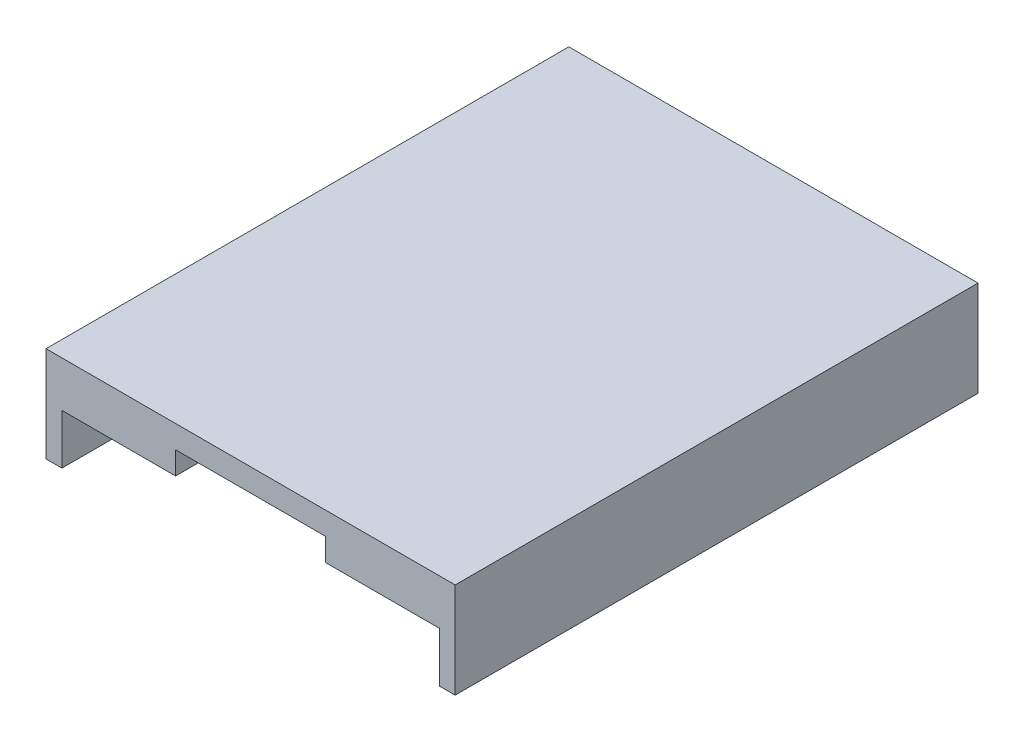
SolidWorks part; units mm, degrees
ref_plane "Front Plane" through (0, 0, 0) normal (0, 0, 1) x (1, 0, 0)
ref_plane "Top Plane" through (0, 0, 0) normal (0, 1, 0) x (1, 0, 0)
ref_plane "Right Plane" through (0, 0, 0) normal (1, 0, 0) x (0, 0, -1)
sketch "Sketch1" plane through (0, 0, 0) normal (0, 0, 1) x (1, 0, 0)
  line L0 (0, 0) -> (0, 21)
  line L1 (0, 21) -> (90, 21)
  line L2 (90, 21) -> (90, 0)
  line L3 (90, 0) -> (86.5, 0)
  line L4 (86.5, 0) -> (86.5, 11)
  line L5 (86.5, 11) -> (61.5, 11)
  line L6 (61.5, 11) -> (61.5, 16)
  line L7 (61.5, 16) -> (28.5, 16)
  line L8 (28.5, 16) -> (28.5, 11)
  line L9 (28.5, 11) -> (3.5, 11)
  line L10 (3.5, 11) -> (3.5, 0)
  line L11 (3.5, 0) -> (0, 0)
  dimension "D1" = 3.5
  dimension "D2" = 90
  dimension "D3" = 3.5
  dimension "D4" = 25
  dimension "D5" = 25
  dimension "D6" = 5
  dimension "D7" = 10
  dimension "D8" = 10
  dimension "D9" = 21
extrude "Boss-Extrude1" add sketch "Sketch1" along normal mid plane 115
